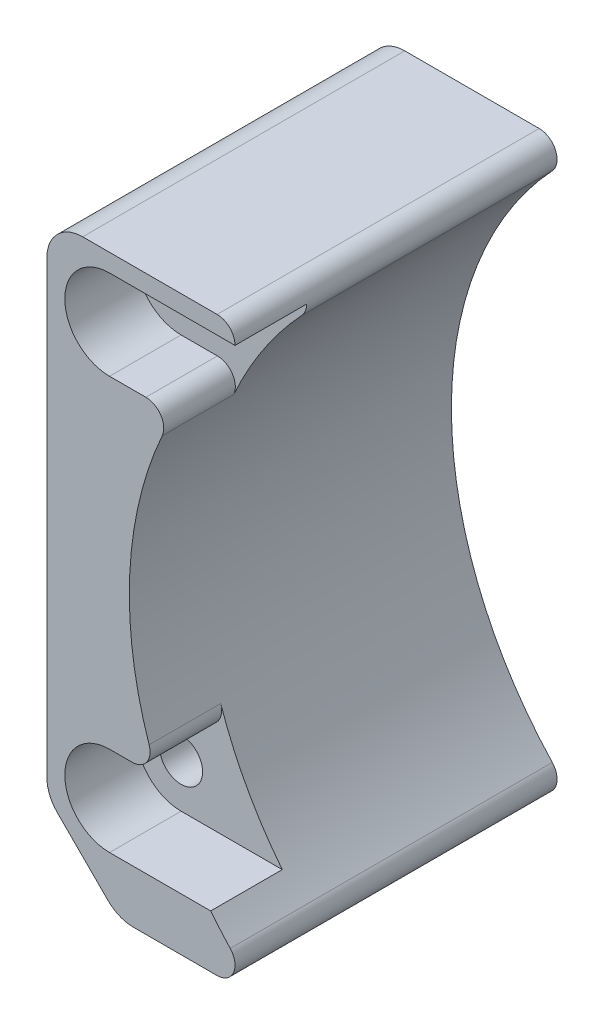
SolidWorks part; units mm, degrees
ref_plane "Front Plane" through (0, 0, 0) normal (0, 0, 1) x (1, 0, 0)
ref_plane "Top Plane" through (0, 0, 0) normal (0, 1, 0) x (1, 0, 0)
ref_plane "Right Plane" through (0, 0, 0) normal (1, 0, 0) x (0, 0, -1)
sketch "Sketch2" plane through (0, 0, 0) normal (0, 0, 1) x (1, 0, 0)
  line L1 (0, 0) -> (19.0567, 0)
  line L2 (0, 0) -> (0, 50.8)
  line L3 (0, 50.8) -> (19.0567, 50.8)
  arc A0 (19.0567, 50.8) -> (19.0567, 0) centre (40.649, 25.4) ccw
  circle A1 centre (40.649, 25.4) radius 2.032 construction
  dimension "D2" = 66.675
  dimension "D1" = 50.8
extrude "Boss-Extrude1" add sketch "Sketch2" along normal up to surface (28.575 mm away)
chamfer "Chamfer1" distance 6.35 angle 45 1 edges at (0, 0, 14.2875)
sketch "Sketch3" plane through (0, 0, 28.575) normal (0, 0, 1) x (1, 0, 0)
  line L0 (19.0567, 50.8) -> (0, 50.8) construction
  line L1 (0, 50.8) -> (0, 6.35) construction
  line L2 (0, 6.35) -> (6.35, 0) construction
  circle A0 centre (5.5562, 45.2438) radius 5.5563 construction
  circle A1 centre (5.5562, 45.2438) radius 1.905
  circle A2 centre (5.5562, 8.6515) radius 5.5562 construction
  circle A3 centre (5.5562, 8.6515) radius 1.905
  dimension "D1" = 11.1125
  dimension "D2" = 3.81
extrude "Cut-Extrude1" cut sketch "Sketch3" against normal through all
fillet "Fillet1" radius 3.175 3 edges at (6.35, 0, 14.2875) (0, 6.35, 14.2875) (0, 50.8, 14.2875)
sketch "Sketch5" [suppressed] plane through (0, 0, 0) normal (0, 0, -1) x (-1, 0, 0)
  line L0 (-5.5562, 49.2125) -> (-17.3176, 49.2125)
  line L1 (-5.5562, 41.275) -> (-11.334, 41.275)
  line L2 (-5.5562, 4.6827) -> (-14.5304, 4.6827)
  line L6 (-5.5563, 12.6202) -> (-9.8583, 12.6202)
  arc A0 (-5.5562, 41.275) -> (-5.5562, 49.2125) centre (-5.5562, 45.2438) ccw
  arc A1 (-19.0567, 0) -> (-19.0567, 50.8) centre (-40.649, 25.4) ccw construction
  arc A5 (-5.5562, 4.6827) -> (-5.5563, 12.6202) centre (-5.5562, 8.6515) ccw
  arc A7 (-14.5304, 4.6827) -> (-9.8583, 12.6202) centre (-40.649, 25.4) ccw
  arc A8 (-11.334, 41.275) -> (-17.3176, 49.2125) centre (-40.649, 25.4) ccw
  dimension "D1" = 7.9375
extrude "Cut-Extrude3" [suppressed] cut sketch "Sketch5" against normal up to surface (6.35 mm away)
sketch "Sketch6" plane through (0, 0, 28.575) normal (0, 0, 1) x (1, 0, 0)
  line L0 (5.5562, 49.2125) -> (17.3176, 49.2125)
  line L1 (5.5562, 41.275) -> (11.334, 41.275)
  line L2 (5.5562, 12.6202) -> (9.8583, 12.6202)
  line L3 (5.5562, 4.6827) -> (14.5304, 4.6827)
  arc A0 (5.5562, 49.2125) -> (5.5562, 41.275) centre (5.5562, 45.2438) ccw
  arc A1 (5.5562, 12.6202) -> (5.5562, 4.6827) centre (5.5562, 8.6515) ccw
  arc A2 (19.0567, 50.8) -> (19.0567, 0) centre (40.649, 25.4) ccw construction
  arc A3 (17.3176, 49.2125) -> (11.334, 41.275) centre (40.649, 25.4) ccw
  arc A4 (9.8583, 12.6202) -> (14.5304, 4.6827) centre (40.649, 25.4) ccw
  dimension "D1" = 7.9375
extrude "Cut-Extrude4" cut sketch "Sketch6" against normal up to surface (6.35 mm away)
fillet "Fillet3" radius 1.5875 2 edges at (19.0567, 0, 14.2875) (19.0567, 50.8, 14.2875)
fillet "Fillet4" [suppressed] radius 1.5875
fillet "Fillet5" radius 1.5875 2 edges at (9.8583, 12.6202, 25.4) (11.334, 41.275, 25.4)
